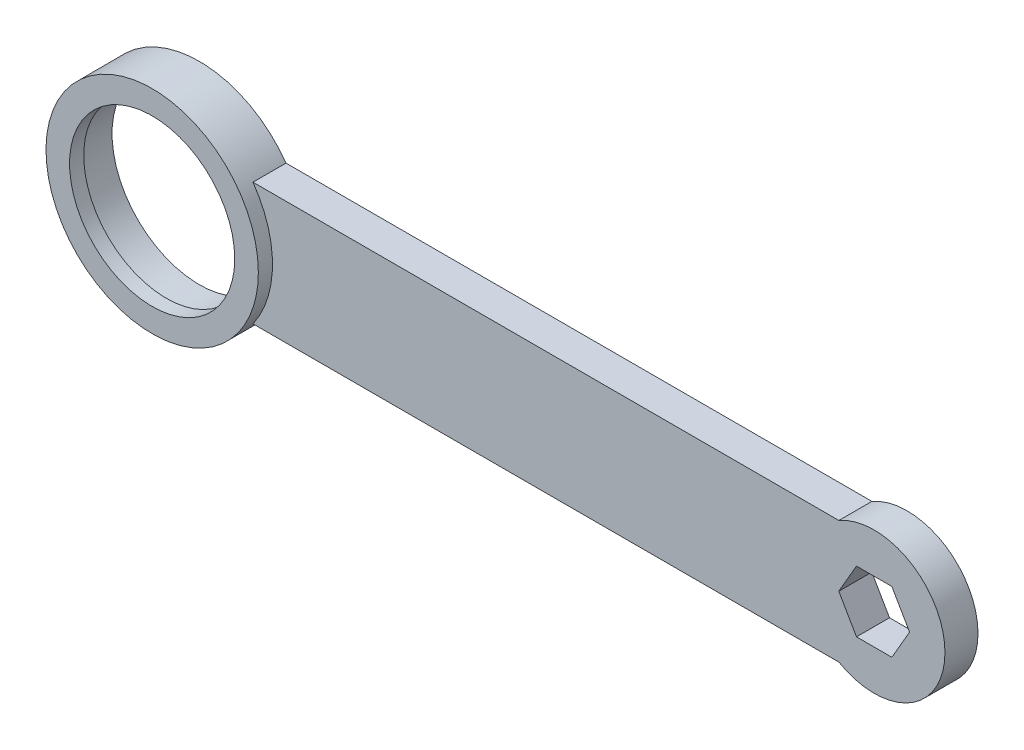
SolidWorks part; units mm, degrees
ref_plane "Front Plane" through (0, 0, 0) normal (0, 0, 1) x (1, 0, 0)
ref_plane "Top Plane" through (0, 0, 0) normal (0, 1, 0) x (1, 0, 0)
ref_plane "Right Plane" through (0, 0, 0) normal (1, 0, 0) x (0, 0, -1)
sketch "Sketch1" plane through (0, 0, 0) normal (0, 0, 1) x (1, 0, 0)
  line L0 (-75, 0) -> (75, 0) construction
  line L2 (-56.6356, 13) -> (67.5167, 13)
  line L3 (-56.6356, 13) -> (-56.6356, -13) construction
  line L4 (-56.6356, -13) -> (67.5167, -13)
  line L5 (67.5167, 13) -> (67.5167, -13) construction
  arc A0 (-56.6356, 13) -> (-56.6356, -13) centre (-75, 0) ccw
  arc A1 (67.5167, -13) -> (67.5167, 13) centre (75, 0) ccw
  point P4 (0, 0)
  point P10 (67.5167, 0)
  dimension "D2" = 45
  dimension "D3" = 30
  dimension "D1" = 150
  dimension "D4" = 26
extrude "Boss-Extrude1" add sketch "Sketch1" along normal blind 7
sketch "Sketch2" plane through (0, 0, 7) normal (0, 0, 1) x (1, 0, 0)
  circle A0 centre (-75, 0) radius 22.5
extrude "Boss-Extrude2" add sketch "Sketch2" along normal blind 3
sketch "Sketch3" plane through (0, 0, 7) normal (0, 0, 1) x (1, 0, 0)
  line L1 (82.5, 0) -> (78.75, 6.4952)
  line L2 (78.75, 6.4952) -> (71.25, 6.4952)
  line L3 (71.25, 6.4952) -> (67.5, 0)
  line L4 (67.5, 0) -> (71.25, -6.4952)
  line L5 (71.25, -6.4952) -> (78.75, -6.4952)
  line L6 (78.75, -6.4952) -> (82.5, 0)
  circle A0 centre (75, 0) radius 7.5 construction
  dimension "D1" = 15
extrude "Cut-Extrude1" cut sketch "Sketch3" against normal through all
sketch "Sketch4" plane through (0, 0, 10) normal (0, 0, 1) x (1, 0, 0)
  circle A0 centre (-75, 0) radius 17.5
  dimension "D1" = 35
extrude "Cut-Extrude2" cut sketch "Sketch4" against normal through all
sketch "Sketch5" plane through (0, 0, 0) normal (0, 0, 1) x (1, 0, 0)
  circle A0 centre (-75, 0) radius 18.5
  dimension "D1" = 37
extrude "Cut-Extrude3" cut sketch "Sketch5" along normal blind 7
sketch "Sketch6" plane through (0, 0, 7) normal (0, 0, -1) x (-1, 0, 0)
  circle A0 centre (75, 0) radius 17.5 construction
  circle A1 centre (75, 0) radius 17.5
extrude "PRINT CAP" [suppressed] add sketch "Sketch6" against normal blind 0.3
